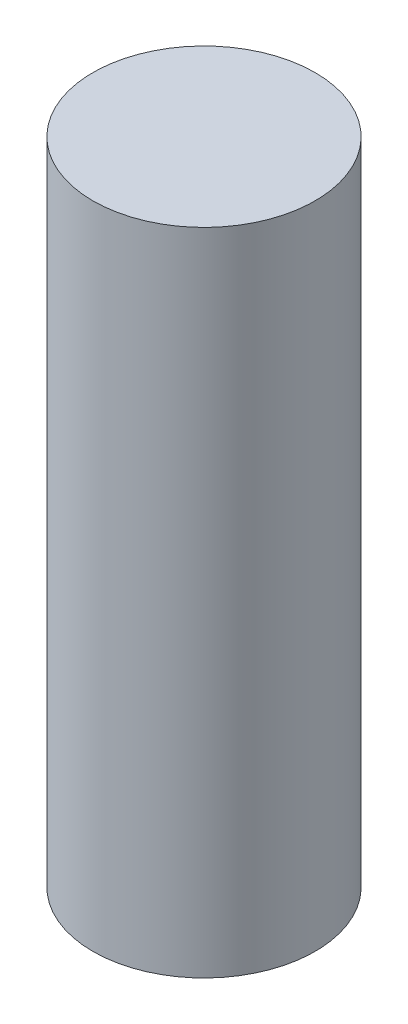
SolidWorks part; units mm, degrees
ref_plane "Front Plane" through (0, 0, 0) normal (0, 0, 1) x (1, 0, 0)
ref_plane "Top Plane" through (0, 0, 0) normal (0, 1, 0) x (1, 0, 0)
ref_plane "Right Plane" through (0, 0, 0) normal (1, 0, 0) x (0, 0, -1)
sketch "Sketch1" plane through (0, 0, 0) normal (0, 1, 0) x (1, 0, 0)
  circle A0 centre (0, 0) radius 20
  dimension "D1" = 40
extrude "Boss-Extrude1" add sketch "Sketch1" along normal blind 117
